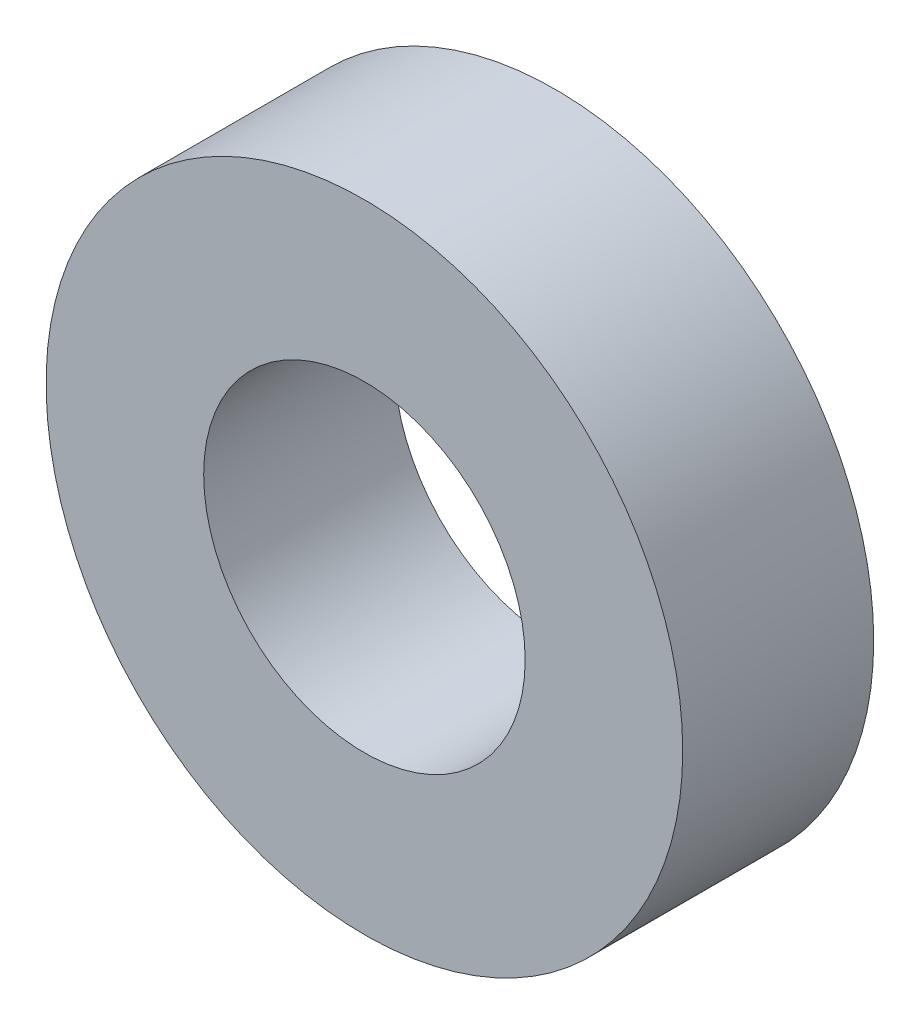
SolidWorks part; units mm, degrees
ref_plane "Plan de face" through (0, 0, 0) normal (0, 0, 1) x (1, 0, 0)
ref_plane "Plan de dessus" through (0, 0, 0) normal (0, 1, 0) x (1, 0, 0)
ref_plane "Plan de droite" through (0, 0, 0) normal (1, 0, 0) x (0, 0, -1)
sketch "Esquisse1" plane through (0, 0, 0) normal (0, 0, 1) x (1, 0, 0)
  circle A0 centre (0, 0) radius 3
  circle A1 centre (0, 0) radius 1.515
  dimension "D1" = 6
  dimension "D2" = 3.03
extrude "Boss.-Extru.1" add sketch "Esquisse1" along normal blind 1.8
